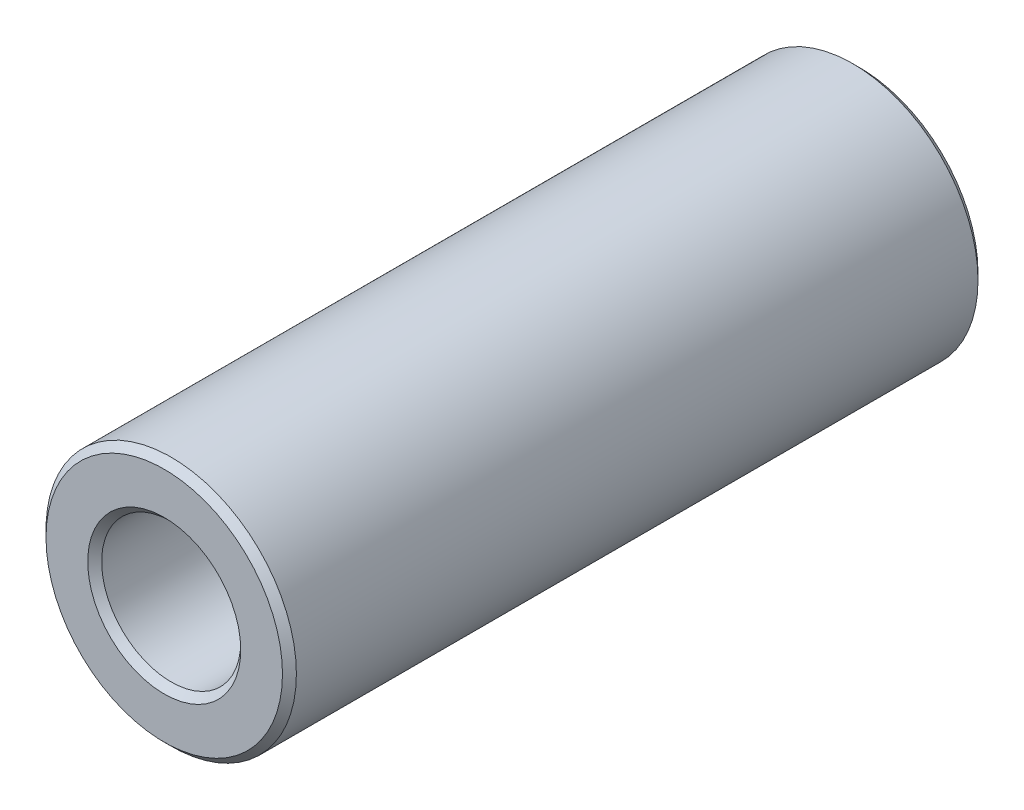
SolidWorks part; units mm, degrees
ref_plane "Front Plane" through (0, 0, 0) normal (0, 0, 1) x (1, 0, 0)
ref_plane "Top Plane" through (0, 0, 0) normal (0, 1, 0) x (1, 0, 0)
ref_plane "Right Plane" through (0, 0, 0) normal (1, 0, 0) x (0, 0, -1)
sketch "Sketch1" plane through (0, 0, 0) normal (0, 0, 1) x (1, 0, 0)
  circle A0 centre (0, 0) radius 5
  circle A1 centre (0, 0) radius 9
  dimension "D1" = 10
  dimension "D2" = 18
extrude "Boss-Extrude1" add sketch "Sketch1" along normal blind 50
chamfer "Chamfer1" distance 0.5 angle 45 4 edges at (9, 0, 0) (9, 0, 50) (5, 0, 0) (5, 0, 50)
